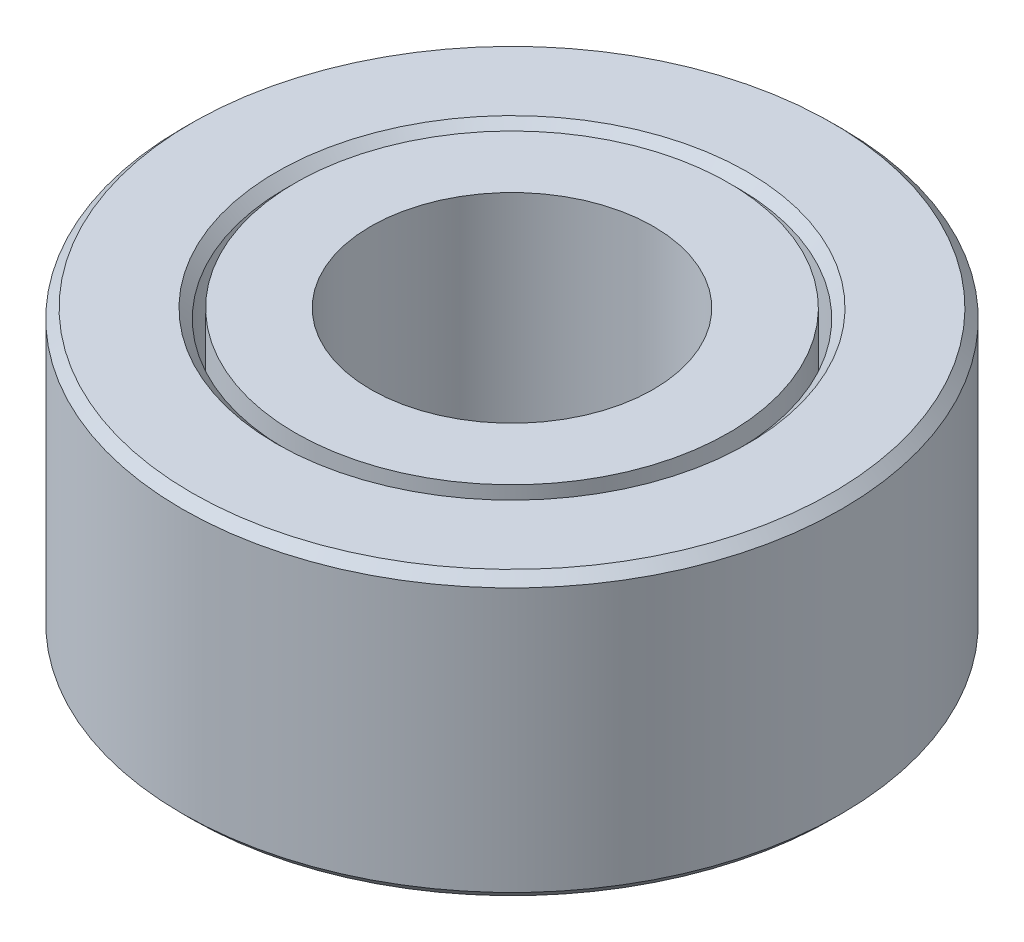
SolidWorks part; units mm, degrees
material "Alliage 1060"
ref_plane "Plan de face" through (0, 0, 0) normal (0, 0, 1) x (1, 0, 0)
ref_plane "Plan de dessus" through (0, 0, 0) normal (0, 1, 0) x (1, 0, 0)
ref_plane "Plan de droite" through (0, 0, 0) normal (1, 0, 0) x (0, 0, -1)
sketch "Esquisse1" plane through (0, 0, 0) normal (0, 1, 0) x (1, 0, 0)
  circle A0 centre (0, 0) radius 3.5
  circle A1 centre (0, 0) radius 1.5
  circle A2 centre (0, 0) radius 2.3
  circle A3 centre (0, 0) radius 2.4
  dimension "D1" = 7
  dimension "D2" = 3
  dimension "D3" = 4.6
  dimension "D4" = 4.8
extrude "Boss.-Extru.1" add sketch "Esquisse1" along normal blind 3 contours A0 A3 | A2 A1
chamfer "Chanfrein1" distance 0.1 angle 45 4 edges at (0, 3, 3.5) (0, 3, 2.4) (0, 0, 2.4) (0, 0, 3.5)
